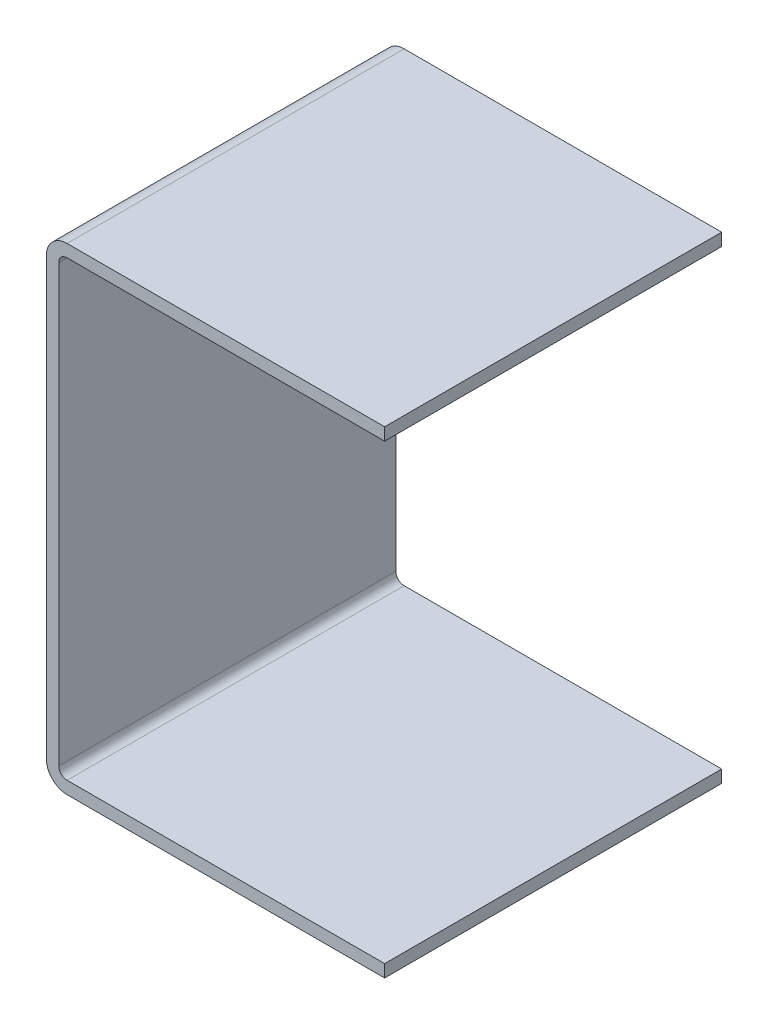
SolidWorks part; units mm, degrees
ref_plane "Plan de face" through (0, 0, 0) normal (0, 0, 1) x (1, 0, 0)
ref_plane "Plan de dessus" through (0, 0, 0) normal (0, 1, 0) x (1, 0, 0)
ref_plane "Plan de droite" through (0, 0, 0) normal (1, 0, 0) x (0, 0, -1)
sketch "Esquisse1" plane through (0, 0, 0) normal (0, 0, 1) x (1, 0, 0)
  line L0 (-47.5751, -19.4302) -> (-47.5751, 85.5698)
  line L1 (-42.5751, 90.5698) -> (33.9249, 90.5698)
  line L2 (33.9249, 90.5698) -> (33.9249, 87.5698)
  line L3 (33.9249, 87.5698) -> (-42.5751, 87.5698)
  line L4 (-44.5751, 85.5698) -> (-44.5751, -19.4302)
  line L5 (-42.5751, -21.4302) -> (33.9249, -21.4302)
  line L6 (33.9249, -21.4302) -> (33.9249, -24.4302)
  line L7 (33.9249, -24.4302) -> (-42.5751, -24.4302)
  arc A0 (-47.5751, -19.4302) -> (-42.5751, -24.4302) centre (-42.5751, -19.4302) ccw
  arc A1 (-47.5751, 85.5698) -> (-42.5751, 90.5698) centre (-42.5751, 85.5698) cw
  arc A2 (-44.5751, -19.4302) -> (-42.5751, -21.4302) centre (-42.5751, -19.4302) ccw
  arc A3 (-42.5751, 87.5698) -> (-44.5751, 85.5698) centre (-42.5751, 85.5698) ccw
  point P10 (-47.5751, -24.4302)
  point P13 (-47.5751, 90.5698)
  point P18 (-44.5751, 87.5698)
  dimension "D7" = 5
  dimension "D8" = 2
  dimension "D1" = 115
  dimension "D2" = 3
  dimension "D3" = 3
  dimension "D4" = 81.5
  dimension "D5" = 81.5
  dimension "D6" = 3
extrude "Extrusion1" add sketch "Esquisse1" along normal mid plane 81.2
